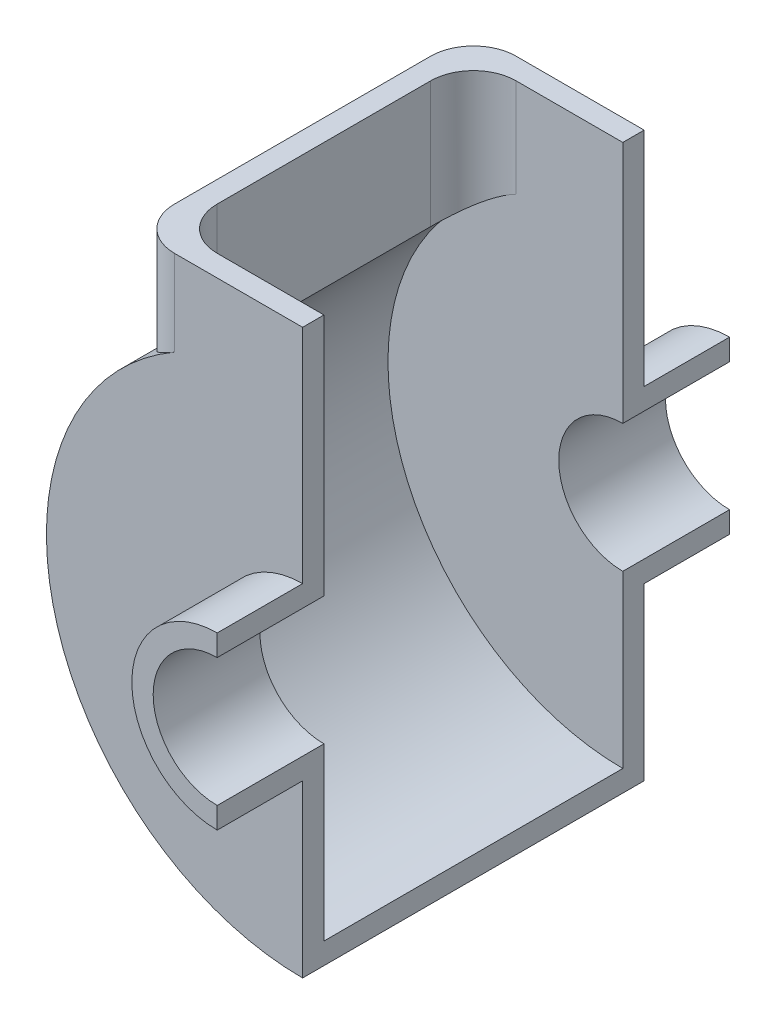
SolidWorks part; units mm, degrees
ref_plane "Płaszczyzna przednia" through (0, 0, 0) normal (0, 0, 1) x (1, 0, 0)
ref_plane "Płaszczyzna górna" through (0, 0, 0) normal (0, 1, 0) x (1, 0, 0)
ref_plane "Płaszczyzna prawa" through (0, 0, 0) normal (1, 0, 0) x (0, 0, -1)
sketch "Szkic1" plane through (0, 0, 0) normal (0, 0, 1) x (1, 0, 0)
  line L0 (0, 15) -> (0, 20)
  line L1 (0, -15) -> (0, -20)
  arc A0 (0, 20) -> (0, -20) centre (0, 0) ccw
  arc A1 (0, 15) -> (0, -15) centre (0, 0) ccw
  dimension "D1" = 20
  dimension "D2" = 15
extrude "Dodanie-wyciągnięcie1" add sketch "Szkic1" along normal blind 25 contours A1 L1 A0 L0
sketch "Szkic2" plane through (0, 0, 0) normal (0, 0, -1) x (-1, 0, 0)
  line L0 (0, 20) -> (0, 72)
  line L1 (0, 72) -> (40, 72)
  line L2 (0, -20) -> (0, -60)
  line L3 (40, 72) -> (40, 44.7214)
  line L6 (0, 20) -> (0, 15)
  line L7 (0, -15) -> (0, -20)
  arc A0 (0, -60) -> (40, 44.7214) centre (0, 0) ccw
  arc A3 (0, -20) -> (0, 20) centre (0, 0) ccw
  arc A4 (0, -15) -> (0, 15) centre (0, 0) ccw
  arc A5 (0, -20) -> (0, 20) centre (0, 0) ccw
  dimension "D1" = 52
  dimension "D2" = 40
  dimension "D3" = 40
  dimension "D4" = 0
extrude "Dodanie-wyciągnięcie2" add sketch "Szkic2" against normal blind 5
ref_plane "Płaszczyzna1" through (0, 0, -35) normal (0, 0, 1) x (1, 0, 0)
mirror "Lustro2" about plane through (0, 0, -35) normal (0, 0, 1) of bodies 102
sketch "Szkic4" plane through (0, 0, 0) normal (0, 0, 1) x (1, 0, 0)
  line L0 (-40, 44.7214) -> (-40, 72) construction
  line L1 (-40, 44.7214) -> (-40, 72)
  arc A0 (-40, 44.7214) -> (0, -60) centre (0, 0) ccw construction
  arc A1 (-40, 44.7214) -> (0, -60) centre (0, 0) ccw
extrude "Wyciągnięcie-cienka ścianka1" add sketch "Szkic4" against normal up to vertex thin
fillet "Zaokrąglenie1" radius 10 4 edges at (-40, 58.3607, 5) (-40, 58.3607, -75) (-35, 57.2132, 0) (-35, 57.2132, -70)
